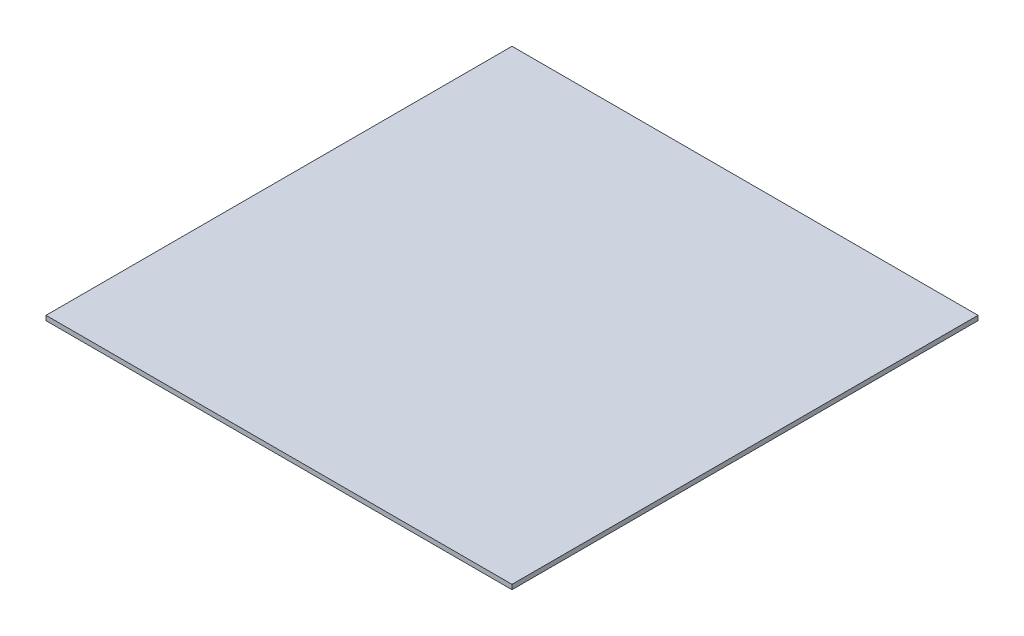
SolidWorks part; units mm, degrees
ref_plane "Front Plane" through (0, 0, 0) normal (0, 0, 1) x (1, 0, 0)
ref_plane "Top Plane" through (0, 0, 0) normal (0, 1, 0) x (1, 0, 0)
ref_plane "Right Plane" through (0, 0, 0) normal (1, 0, 0) x (0, 0, -1)
sketch "Sketch1" plane through (0, 0, 0) normal (0, 1, 0) x (1, 0, 0)
  line L1 (-15240, 15240) -> (15240, 15240)
  line L2 (-15240, 15240) -> (-15240, -15240)
  line L3 (-15240, -15240) -> (15240, -15240)
  line L4 (15240, 15240) -> (15240, -15240)
  line L5 (-15240, 15240) -> (15240, -15240) construction
  line L6 (-15240, -15240) -> (15240, 15240) construction
  point P0 (0, 0)
  dimension "D1" = 30480
  dimension "D2" = 30480
extrude "Extrude1" add sketch "Sketch1" against normal blind 304.8
